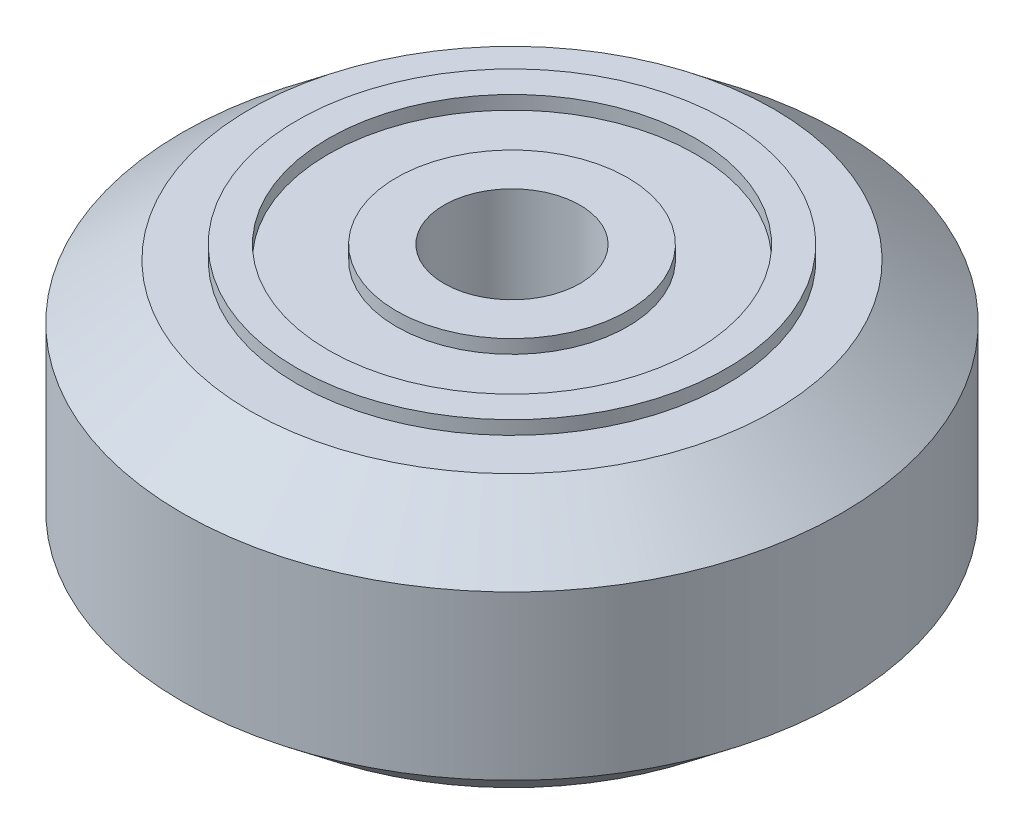
SolidWorks part; units mm, degrees
ref_plane "Front Plane" through (0, 0, 0) normal (0, 0, 1) x (1, 0, 0)
ref_plane "Top Plane" through (0, 0, 0) normal (0, 1, 0) x (1, 0, 0)
ref_plane "Right Plane" through (0, 0, 0) normal (1, 0, 0) x (0, 0, -1)
sketch "Sketch1" plane through (0, 0, 0) normal (0, 0, 1) x (1, 0, 0)
  line L0 (0, 0) -> (-8.9994, 0)
  line L1 (-8.9994, 0) -> (-12.125, 2.5)
  line L2 (-12.125, 2.5) -> (-12.125, 8.5)
  line L3 (-12.125, 8.5) -> (-8.9994, 11)
  line L4 (-8.9994, 11) -> (0, 11)
  line L5 (0, 11) -> (0, 0)
  point P4 (-12.125, 5.5)
  point P8 (0, 5.5)
  dimension "D1" = 12.125
  dimension "D2" = 11
  dimension "D3" = 6
revolve "Revolve1" add sketch "Sketch1" angle 360 about L5
ref_plane "Plane1" through (0, 5.5, 0) normal (0, 1, 0) x (1, 0, 0)
sketch "Sketch4" plane through (0, 11, 0) normal (0, 1, 0) x (1, 0, 0)
  circle A0 centre (0, 0) radius 7.9
  circle A1 centre (0, 0) radius 10.4297
extrude "Cut-Extrude1" cut sketch "Sketch4" against normal blind 0.5
sketch "Sketch5" plane through (0, 11, 0) normal (0, 1, 0) x (1, 0, 0)
  circle A0 centre (0, 0) radius 6.75
extrude "Cut-Extrude2" cut sketch "Sketch5" against normal blind 0.5
sketch "Sketch6" plane through (0, 10.5, 0) normal (0, 1, 0) x (1, 0, 0)
  circle A0 centre (0, 0) radius 4.25
extrude "Boss-Extrude1" add sketch "Sketch6" along normal blind 0.5
mirror "Mirror1" about plane through (0, 5.5, 0) normal (0, 1, 0) of "Cut-Extrude2", "Cut-Extrude1", "Boss-Extrude1"
sketch "Sketch7" plane through (0, 11, 0) normal (0, 1, 0) x (1, 0, 0)
  circle A0 centre (0, 0) radius 2.5
extrude "Cut-Extrude3" cut sketch "Sketch7" against normal through all
